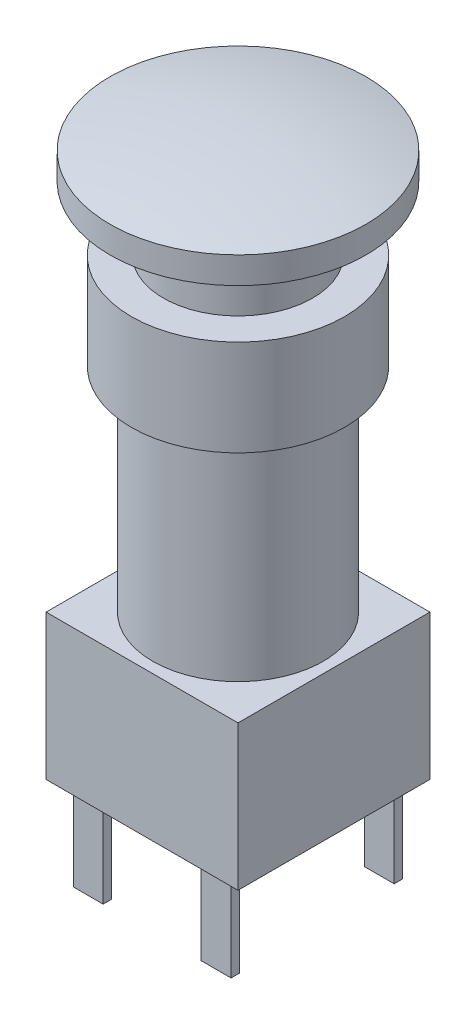
SolidWorks part; units mm, degrees
ref_plane "Plan de face" through (0, 0, 0) normal (0, 0, 1) x (1, 0, 0)
ref_plane "Plan de dessus" through (0, 0, 0) normal (0, 1, 0) x (1, 0, 0)
ref_plane "Plan de droite" through (0, 0, 0) normal (1, 0, 0) x (0, 0, -1)
sketch "Esquisse1" plane through (0, 0, 0) normal (0, 0, 1) x (1, 0, 0)
  line L0 (0, 19) -> (0, 0)
  line L1 (8, 0) -> (0, 0) construction
  line L2 (7, 15) -> (7, 9)
  line L3 (10, 0) -> (8, 0)
  line L4 (7, 9) -> (10, 9)
  line L5 (7, 15) -> (12, 15)
  line L6 (12, 15) -> (12, 17.5)
  line L7 (0, 19) -> (-6.5655, 19) construction
  line L8 (0, 19) -> (0, 45.9128) construction
  line L9 (10, 9) -> (10, 0)
  line L10 (8, 0) -> (8, -20)
  line L11 (8, -20) -> (0, -20)
  line L12 (0, -20) -> (0, 0)
  arc A0 (0, 19) -> (12, 17.5) centre (0, -29.75) cw
  dimension "D3" = 9
  dimension "D1" = 24
  dimension "D2" = 19
  dimension "D4" = 20
  dimension "D5" = 16
  dimension "D6" = 14
  dimension "D7" = 6
  dimension "D8" = 2.5
  dimension "D9" = 20
revolve "Révolution1" add sketch "Esquisse1" angle 360 about L8
sketch "Esquisse2" plane through (0, -20, 0) normal (0, -1, 0) x (1, 0, 0)
  line L1 (-9, -9) -> (9, -9)
  line L2 (-9, -9) -> (-9, 9)
  line L3 (-9, 9) -> (9, 9)
  line L4 (9, -9) -> (9, 9)
  line L5 (-9, -9) -> (9, 9) construction
  line L6 (-9, 9) -> (9, -9) construction
  point P0 (0, 0)
  dimension "D1" = 18
  dimension "D2" = 18
extrude "Boss.-Extru.1" add sketch "Esquisse2" along normal blind 13.6
sketch "Esquisse3" plane through (0, -33.6, 0) normal (0, -1, 0) x (1, 0, 0)
  line L0 (0, 9) -> (0, 0) construction
  line L1 (-7.4, 7.25) -> (-4.6, 7.25)
  line L2 (-7.4, 7.25) -> (-7.4, 8.05)
  line L3 (-7.4, 8.05) -> (-4.6, 8.05)
  line L4 (-4.6, 7.25) -> (-4.6, 8.05)
  line L5 (9, 9) -> (-9, 9) construction
  line L6 (0, 0) -> (-9, 0) construction
  line L7 (-9, 9) -> (-9, -9) construction
  line L8 (4.6, 7.25) -> (4.6, 8.05)
  line L9 (7.4, 8.05) -> (4.6, 8.05)
  line L10 (7.4, 7.25) -> (7.4, 8.05)
  line L11 (7.4, 7.25) -> (4.6, 7.25)
  line L12 (7.4, -7.25) -> (4.6, -7.25)
  line L13 (7.4, -7.25) -> (7.4, -8.05)
  line L14 (7.4, -8.05) -> (4.6, -8.05)
  line L15 (4.6, -7.25) -> (4.6, -8.05)
  line L16 (-4.6, -7.25) -> (-4.6, -8.05)
  line L17 (-7.4, -8.05) -> (-4.6, -8.05)
  line L18 (-7.4, -7.25) -> (-7.4, -8.05)
  line L19 (-7.4, -7.25) -> (-4.6, -7.25)
  dimension "D1" = 2.8
  dimension "D2" = 12
  dimension "D3" = 15.3
  dimension "D4" = 0.8
extrude "Boss.-Extru.2" add sketch "Esquisse3" along normal blind 8.4
